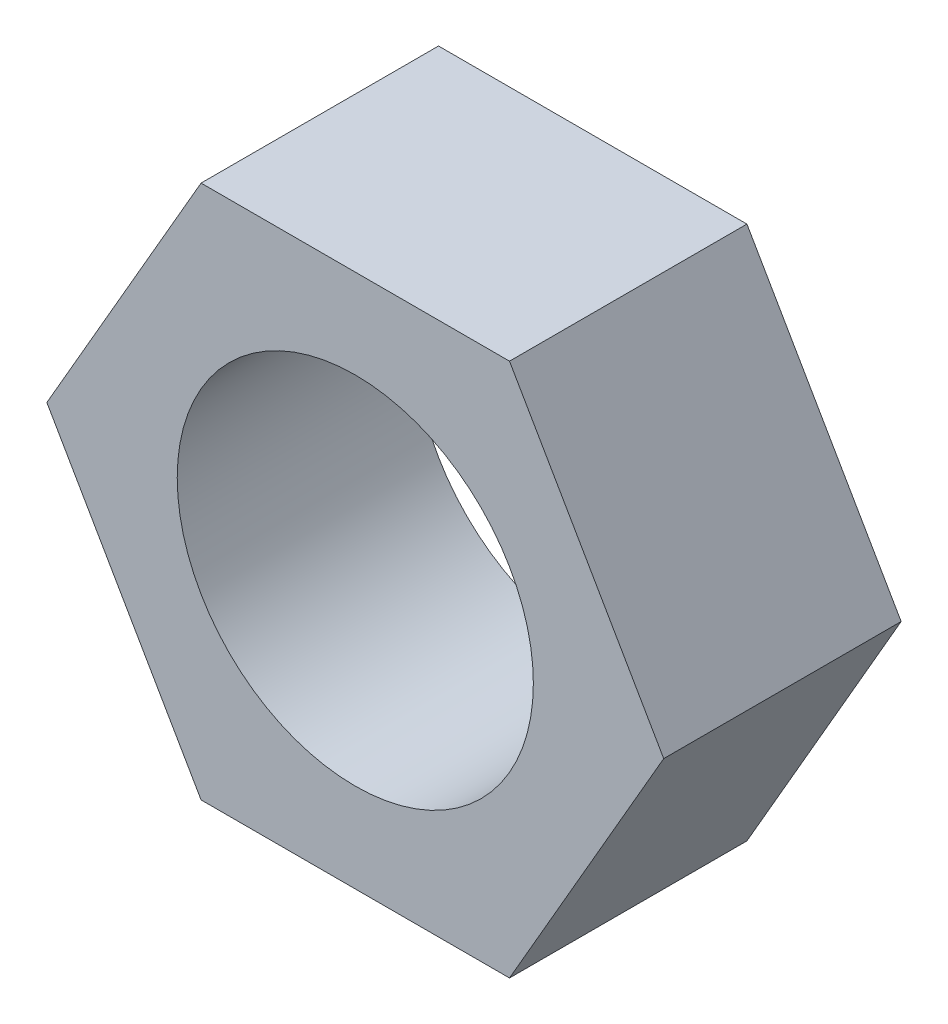
SolidWorks part; units mm, degrees
ref_plane "Front Plane" through (0, 0, 0) normal (0, 0, 1) x (1, 0, 0)
ref_plane "Top Plane" through (0, 0, 0) normal (0, 1, 0) x (1, 0, 0)
ref_plane "Right Plane" through (0, 0, 0) normal (1, 0, 0) x (0, 0, -1)
sketch "Sketch1" plane through (0, 0, 0) normal (0, 0, 1) x (1, 0, 0)
  line L1 (2.5981, 0) -> (1.299, 2.25)
  line L2 (1.299, 2.25) -> (-1.299, 2.25)
  line L3 (-1.299, 2.25) -> (-2.5981, 0)
  line L4 (-2.5981, 0) -> (-1.299, -2.25)
  line L5 (-1.299, -2.25) -> (1.299, -2.25)
  line L6 (1.299, -2.25) -> (2.5981, 0)
  circle A0 centre (0, 0) radius 2.25 construction
  circle A1 centre (0, 0) radius 1.5
  dimension "D1" = 4.5
  dimension "D2" = 3
extrude "Boss-Extrude1" add sketch "Sketch1" along normal blind 2
